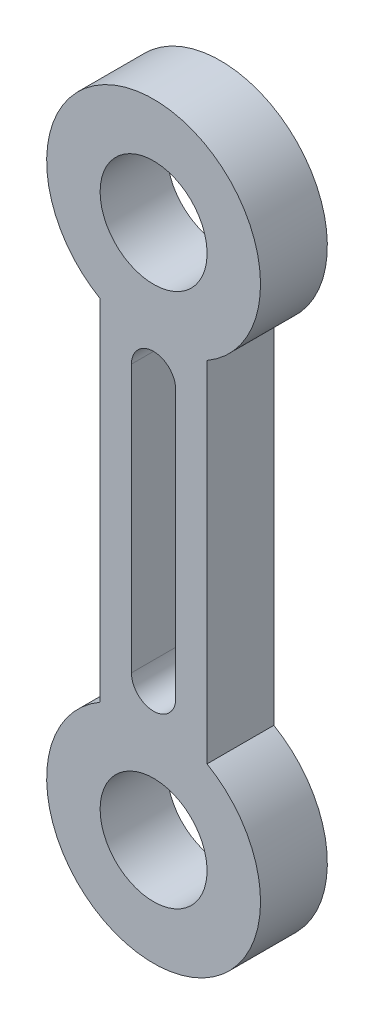
SolidWorks part; units mm, degrees
ref_plane "前视基准面" through (0, 0, 0) normal (0, 0, 1) x (1, 0, 0)
ref_plane "上视基准面" through (0, 0, 0) normal (0, 1, 0) x (1, 0, 0)
ref_plane "右视基准面" through (0, 0, 0) normal (1, 0, 0) x (0, 0, -1)
sketch "草图1" plane through (0, 0, 0) normal (0, 0, 1) x (1, 0, 0)
  line L1 (-4, 0) -> (4, 0)
  line L2 (-4, 0) -> (-4, -40)
  line L3 (-4, -40) -> (4, -40)
  line L4 (4, 0) -> (4, -40)
  circle A0 centre (0, 0) radius 8
  circle A1 centre (0, -40) radius 8
  dimension "D1" = 0
  dimension "D5" = 0
  dimension "D2" = 4
  dimension "D3" = 4
  dimension "D4" = 40
extrude "凸台-拉伸1" add sketch "草图1" along normal blind 5 contours L4 A0 L2 L1 | A1 L4 A0 L2 | L2 A0 L4 L1 | L4 A1 L2 L3 | L2 A1 L4 L3
sketch "草图3" plane through (0, 0, 0) normal (0, 0, -1) x (-1, 0, 0)
  circle A0 centre (0, 0) radius 4
  circle A1 centre (0, -40) radius 4
extrude "切除-拉伸1" cut sketch "草图3" against normal through all
sketch "草图4" plane through (0, 0, 0) normal (0, 0, -1) x (-1, 0, 0)
  line L0 (0, -10) -> (0, -30) construction
  line L1 (1.658, -10) -> (1.658, -30)
  line L2 (-1.658, -10) -> (-1.658, -30)
  line L3 (0, -40) -> (0, 0) construction
  arc A0 (1.658, -10) -> (-1.658, -10) centre (0, -10) ccw
  arc A1 (-1.658, -30) -> (1.658, -30) centre (0, -30) ccw
  point P2 (0, -20)
  dimension "D1" = 10
  dimension "D2" = 10
  dimension "D3" = 0
extrude "切除-拉伸2" cut sketch "草图4" against normal through all
